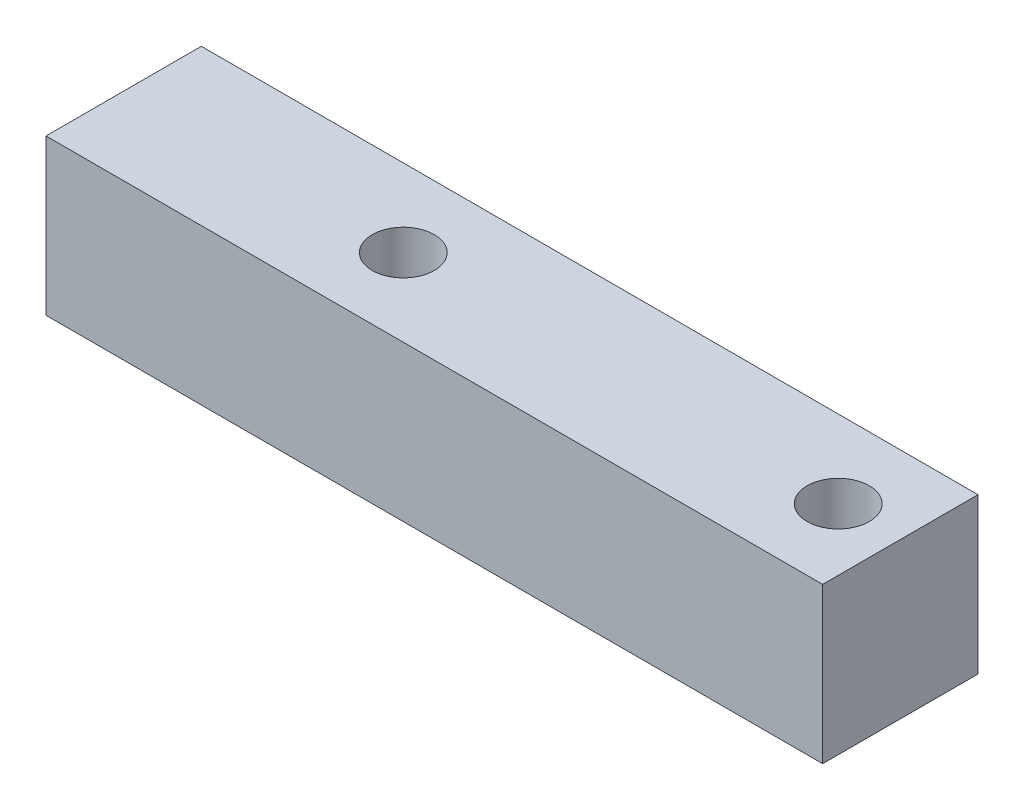
SolidWorks part; units mm, degrees
material "Delrin 2700 NC010, Low Viscosity Acetal Copolymer (SS)"
ref_plane "Front Plane" through (0, 0, 0) normal (0, 0, 1) x (1, 0, 0)
ref_plane "Top Plane" through (0, 0, 0) normal (0, 1, 0) x (1, 0, 0)
ref_plane "Right Plane" through (0, 0, 0) normal (1, 0, 0) x (0, 0, -1)
sketch "Sketch1" plane through (0, 0, 0) normal (0, 0, 1) x (1, 0, 0)
  line L0 (39.6875, 0) -> (30.1625, 0) construction
  line L1 (39.6875, -7.9375) -> (-39.6875, -7.9375)
  line L2 (39.6875, -7.9375) -> (39.6875, 7.9375)
  line L3 (39.6875, 7.9375) -> (-39.6875, 7.9375)
  line L4 (-39.6875, -7.9375) -> (-39.6875, 7.9375)
  line L5 (39.6875, -7.9375) -> (-39.6875, 7.9375) construction
  line L6 (39.6875, 7.9375) -> (-39.6875, -7.9375) construction
  line L7 (30.1625, 0) -> (4.7625, 0) construction
  point P0 (0, 0)
  dimension "D1" = 79.375
  dimension "D2" = 15.875
extrude "Boss-Extrude1" add sketch "Sketch1" along normal mid plane 15.875
sketch "Sketch2" plane through (-39.6875, 0, 0) normal (-1, 0, 0) x (0, 0, 1)
  circle A0 centre (0, 0) radius 4.7625
  dimension "D1" = 9.525
extrude "Cut-Extrude1" cut sketch "Sketch2" against normal blind 19.05
sketch "Sketch3" plane through (0, 7.9375, 0) normal (0, 1, 0) x (1, 0, 0)
  line L0 (39.6875, -7.9375) -> (39.6875, 7.9375) construction
  line L1 (-11.1125, 0) -> (39.6875, 0) construction
  circle A0 centre (33.3375, 0) radius 3.175
  circle A1 centre (-11.1125, 0) radius 3.175
  dimension "D1" = 44.45
  dimension "D2" = 6.35
  dimension "D3" = 6.35
extrude "Cut-Extrude2" cut sketch "Sketch3" against normal through all
